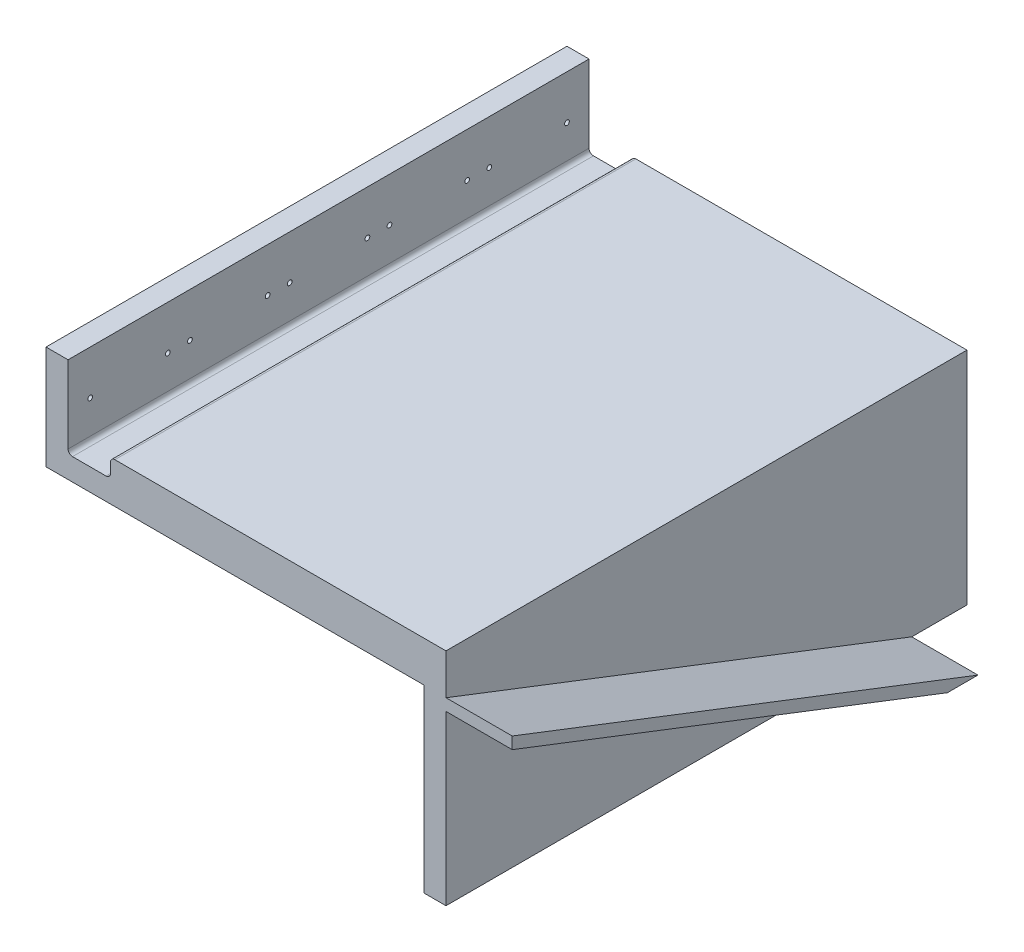
SolidWorks part; units mm, degrees
ref_plane "Front Plane" through (0, 0, 0) normal (0, 0, 1) x (1, 0, 0)
ref_plane "Top Plane" through (0, 0, 0) normal (0, 1, 0) x (1, 0, 0)
ref_plane "Right Plane" through (0, 0, 0) normal (1, 0, 0) x (0, 0, -1)
sketch "Sketch2" plane through (0, 0, 0) normal (0, 0, 1) x (1, 0, 0)
  line L0 (-117.2626, 0) -> (118.7133, 0) construction
  line L1 (0, 0) -> (0, 22.2127)
  line L2 (0, 22.2127) -> (-10, 22.2127)
  line L3 (-10, 22.2127) -> (-10, -24.7873)
  line L4 (-10, -24.7873) -> (171.2, -24.7873)
  line L5 (171.2, -24.7873) -> (171.2, -6.3873)
  line L6 (171.2, -6.3873) -> (19.2, -6.3873)
  line L7 (19.2, -6.3873) -> (19.2, -14.7873)
  line L8 (19.2, -14.7873) -> (0, -14.7873)
  line L9 (0, -14.7873) -> (0, 0)
  dimension "D1" = 10
  dimension "D2" = 47
  dimension "D3" = 19.2
  dimension "D4" = 8.4
  dimension "D5" = 10
  dimension "D6" = 152
extrude "Boss-Extrude1" add sketch "Sketch2" along normal blind 236
sketch "Sketch5" plane through (0, 0, 0) normal (1, 0, 0) x (0, 0, -1)
  line L0 (-180.1737, 2.2127) -> (14.3405, 2.2127) construction
  line L1 (-236, -6.3873) -> (0, -6.3873) construction
  line L2 (-236, -6.3873) -> (0, -6.3873)
  line L3 (-236, -14.7873) -> (0, -14.7873) construction
  line L4 (-236, -14.7873) -> (0, -14.7873)
  line L5 (-10, 27.0173) -> (-10, -31.5916) construction
  line L6 (0, 55) -> (0, -55) construction
  line L7 (-45.2, 27.0173) -> (-45.2, -27.4923) construction
  circle A0 centre (-10, 2.2127) radius 1.075
  circle A1 centre (-45.2, 2.2127) radius 1.075
  circle A2 centre (-55.2, 2.2127) radius 1.075
  circle A3 centre (-90.4, 2.2127) radius 1.075
  circle A4 centre (-100.4, 2.2127) radius 1.075
  circle A5 centre (-135.6, 2.2127) radius 1.075
  circle A6 centre (-145.6, 2.2127) radius 1.075
  circle A7 centre (-180.8, 2.2127) radius 1.075
  circle A8 centre (-190.8, 2.2127) radius 1.075
  circle A9 centre (-226, 2.2127) radius 1.075
  dimension "D3" = 2.15
  dimension "D5" = 5
  dimension "D1" = 17
  dimension "D2" = 10
  dimension "D4" = 35.2
extrude "Cut-Extrude1" cut sketch "Sketch5" against normal mid plane 170 contours A0 | A1 | A2 | A5 | A3 | A4 | A6 | A7 | A8 | A9
fillet "Fillet1" radius 2 3 edges at (19.2, -6.3873, 118) (19.2, -14.7873, 118) (0, -14.7873, 118)
sketch "Sketch7" plane through (0, -6.3873, 0) normal (0, 1, 0) x (1, 0, 0)
  line L0 (171.2, -236) -> (161.2, -236)
  line L1 (171.2, -236) -> (21.2, -236) construction
  line L2 (161.2, -236) -> (161.2, 0)
  line L3 (-55, 0) -> (55, 0) construction
  line L4 (171.2, 0) -> (21.2, 0)
  line L5 (21.2, 0) -> (21.2, -236)
  line L6 (21.2, -236) -> (171.2, -236)
  line L7 (171.2, -236) -> (171.2, 0)
  line L11 (171.2, -236) -> (171.2, 0)
  line L12 (161.2, 0) -> (171.2, 0)
  dimension "D2" = 10
  dimension "D1" = 0
extrude "Boss-Extrude2" add sketch "Sketch7" against normal offset from surface (100 mm away) 100 up to face at (96.2, -6.3873, 118)
sketch "Sketch8" plane through (171.2, 0, 0) normal (1, 0, 0) x (0, 0, -1)
  line L0 (-236, -106.3873) -> (0, -106.3873) construction
  line L4 (-236, -24.7873) -> (-236, -30.1482)
  line L6 (-236, -24.7873) -> (-25, -106.3873)
  line L7 (-236, -106.3873) -> (-236, -6.3873) construction
  line L8 (-236, -30.1482) -> (-38.8621, -106.3873)
  line L9 (-38.8621, -106.3873) -> (-25, -106.3873)
  dimension "D1" = 25
  dimension "D2" = 5
extrude "Boss-Extrude3" add sketch "Sketch8" along normal blind 30
